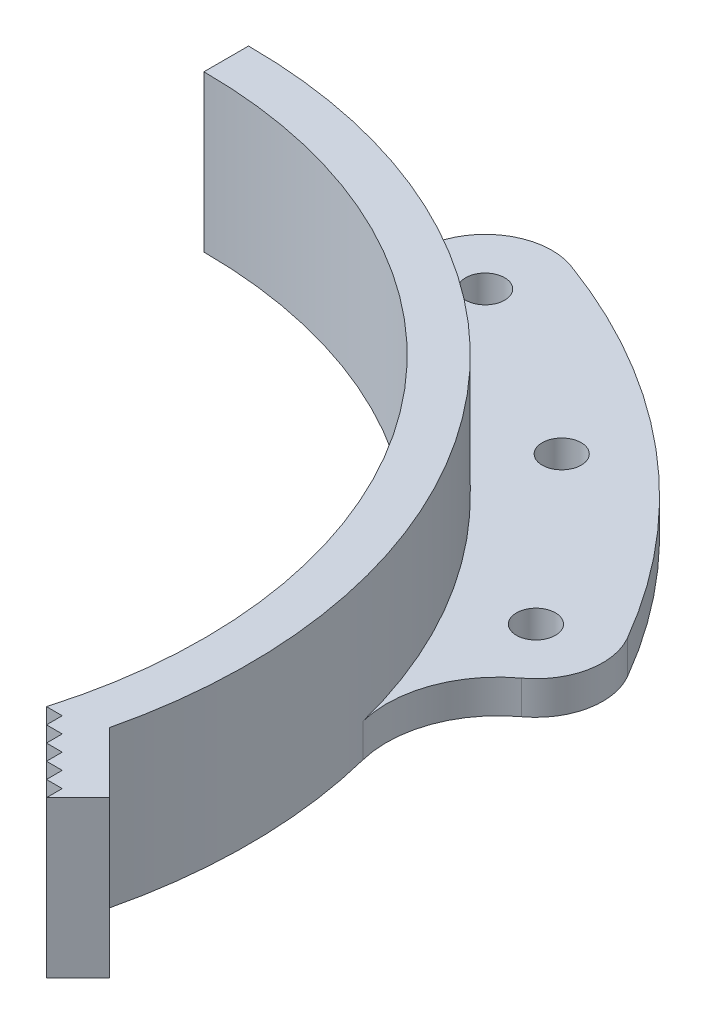
SolidWorks part; units mm, degrees
ref_plane "Спереди" through (0, 0, 0) normal (0, 0, 1) x (1, 0, 0)
ref_plane "Сверху" through (0, 0, 0) normal (0, 1, 0) x (1, 0, 0)
ref_plane "Справа" through (0, 0, 0) normal (1, 0, 0) x (0, 0, -1)
sketch "Эскиз1" plane through (0, 0, 0) normal (0, 1, 0) x (1, 0, 0)
  line L0 (0, 0) -> (18.4691, 50.7434) construction
  line L1 (0, 0) -> (34.7105, 41.3664) construction
  line L2 (0, 0) -> (41.5692, 24) construction
  line L4 (0, 48) -> (0, 52)
  circle A0 centre (34.7105, 41.3664) radius 1.75
  circle A2 centre (18.4691, 50.7434) radius 1.75
  circle A3 centre (46.7654, 27) radius 1.75
  arc A4 (41.5692, 24) -> (51.9615, 30) centre (46.7654, 27) ccw
  arc A5 (41.5692, 24) -> (0, 48) centre (0, 0) ccw construction
  arc A6 (41.5692, 24) -> (0, 48) centre (0, 0) ccw
  arc A8 (20.5212, 56.3816) -> (12.4748, 50.4815) centre (18.4691, 50.7434) ccw
  arc A11 (12.4748, 50.4815) -> (0, 52) centre (0, 0) ccw
  arc A14 (51.9615, 30) -> (20.5212, 56.3816) centre (0, 0) ccw
  point P11 (0, 0)
  dimension "D6" = 60
  dimension "D7" = 3
  dimension "D1" = 20
  dimension "D2" = 3.5
  dimension "D4" = 48
  dimension "D5" = 52
  dimension "D8" = 20
extrude "Бобышка-Вытянуть1" add sketch "Эскиз1" along normal blind 3
sketch "Эскиз2" plane through (0, 3, 0) normal (0, 1, 0) x (1, 0, 0)
  line L0 (0, 52) -> (0, 48) construction
  line L1 (49.3028, -19.4192) -> (49.3028, -18.005)
  line L2 (0, 44) -> (0, 48)
  line L3 (49.3028, -19.4192) -> (52.1313, -16.5908)
  line L4 (49.3028, -19.4192) -> (-17.101, 46.9846) construction
  line L5 (42.2318, -12.3482) -> (49.3028, -19.4192) construction
  line L6 (52.1313, -16.5908) -> (46.6877, -11.1472)
  line L7 (49.3028, -18.005) -> (47.8886, -18.005)
  line L8 (47.8886, -16.5908) -> (46.4744, -16.5908)
  line L9 (47.8886, -18.005) -> (47.8886, -16.5908)
  line L10 (46.4744, -15.1766) -> (45.0602, -15.1766)
  line L11 (46.4744, -16.5908) -> (46.4744, -15.1766)
  line L12 (45.0602, -13.7624) -> (43.646, -13.7624)
  line L13 (45.0602, -15.1766) -> (45.0602, -13.7624)
  line L14 (43.646, -12.3482) -> (42.2318, -12.3482)
  line L15 (43.646, -13.7624) -> (43.646, -12.3482)
  line L16 (0, 0) -> (-17.101, 46.9846) construction
  line L17 (0, 0) -> (0, 44) construction
  arc A0 (42.2318, -12.3482) -> (0, 44) centre (0, 0) ccw
  arc A1 (46.6877, -11.1472) -> (0, 48) centre (0, 0) ccw
  arc A2 (41.5692, 24) -> (0, 48) centre (0, 0) ccw construction
  circle A3 centre (0, 0) radius 44 construction
  circle A5 centre (0, 0) radius 50 construction
  dimension "D1" = 4
  dimension "D2" = 20
  dimension "D8" = 100
  dimension "D4" = 1
  dimension "D5" = 5
  dimension "D6" = 4
extrude "Выступ для захвата" add sketch "Эскиз2" along normal blind 11 and the other way blind 3
fillet "Fillet1" radius 10 1 edges at (41.5692, 1.5, -24)
